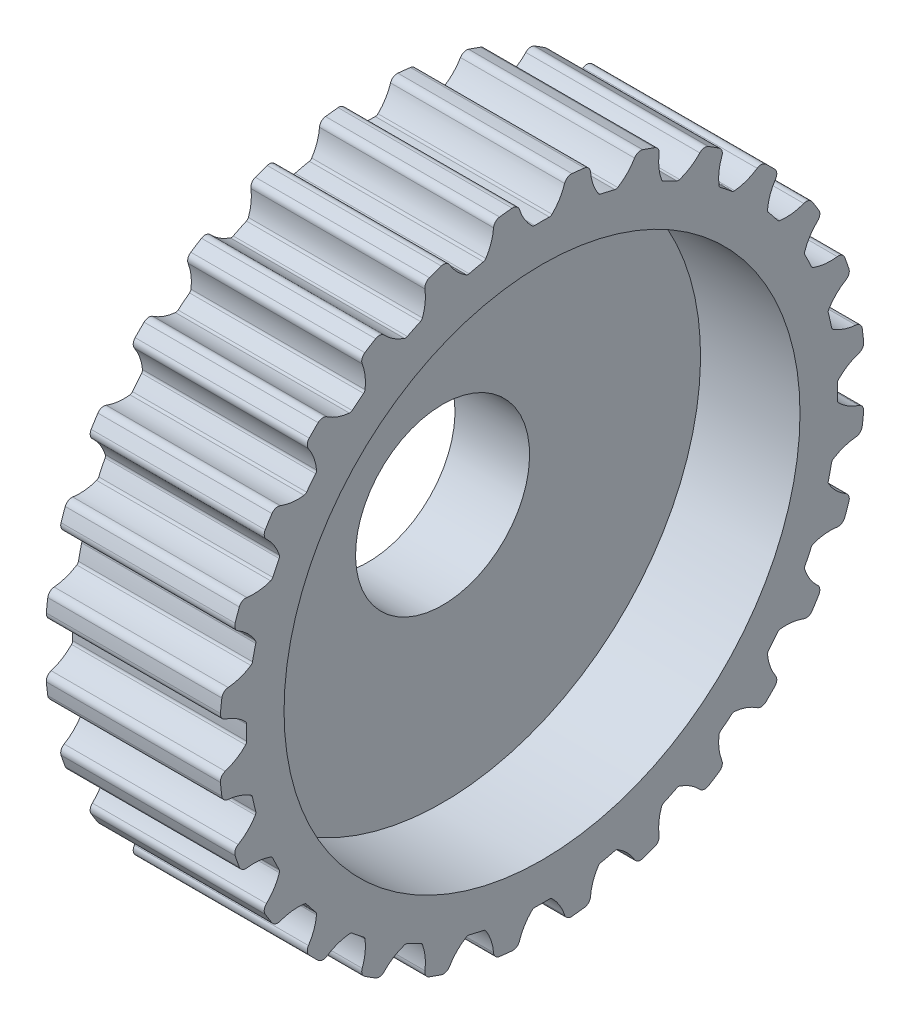
SolidWorks part; units mm, degrees
material "Vero PureWhite"
ref_plane "前视基准面" through (0, 0, 0) normal (0, 0, 1) x (1, 0, 0)
ref_plane "上视基准面" through (0, 0, 0) normal (0, 1, 0) x (1, 0, 0)
ref_plane "右视基准面" through (0, 0, 0) normal (1, 0, 0) x (0, 0, -1)
other "Configuration Table"
ref_plane "基准面1" through (0, 0, 0) normal (0, 0, 1) x (1, 0, 0)
sketch "草图1" plane through (0, 0, 0) normal (0, 0, 1) x (1, 0, 0)
  line L0 (0, 0) -> (0, 10)
  line L1 (0, 10) -> (1, 10)
  line L2 (1, 10) -> (1, 12.8583)
  line L3 (1, 12.8583) -> (0.4955, 14.7412)
  line L4 (0.4955, 14.7412) -> (1.4614, 15)
  line L5 (1.4614, 15) -> (2, 12.99)
  line L6 (2, 12.99) -> (9, 12.99)
  line L7 (9, 12.99) -> (9.5386, 15)
  line L8 (9.5386, 15) -> (10.5045, 14.7412)
  line L9 (10.5045, 14.7412) -> (10, 12.8583)
  line L10 (10, 12.8583) -> (10, 10)
  line L11 (10, 10) -> (11, 10)
  line L12 (11, 10) -> (11, 0)
  line L13 (11, 0) -> (0, 0)
  line L14 (11, 0) -> (0, 0) construction
revolve "旋转1" add sketch "草图1" angle 360 about L14
ref_plane "基准面2" through (0, 0, 0) normal (0, 0, 1) x (1, 0, 0)
sketch "草图2" plane through (0, 0, 0) normal (0, 0, 1) x (1, 0, 0)
  line L0 (0, 0) -> (0, 3.5)
  line L1 (0, 3.5) -> (11, 3.5)
  line L2 (11, 3.5) -> (11, 0)
  line L3 (11, 0) -> (0, 0)
  line L4 (11, 0) -> (0, 0) construction
  dimension "D1" = 3.5
revolve "切除-旋转1" cut sketch "草图2" angle 360 about L4
ref_plane "基准面3" through (2, 0, 0) normal (1, 0, 0) x (0, 0, -1)
sketch "草图3" plane through (2, 0, 0) normal (1, 0, 0) x (0, 0, -1)
  circle A0 centre (0, 0) radius 17.99
  arc A1 (-12.9343, 1.2013) -> (-12.7398, 0.9084) centre (-12.6555, 1.1754) ccw
  arc A2 (-12.7398, 0.9084) -> (-11.9188, 0.4022) centre (-13.3344, -0.975) cw
  arc A3 (-11.9188, 0.4022) -> (-11.8764, 0.2939) centre (-12.0263, 0.2976) cw
  arc A4 (-11.8764, 0.2939) -> (-11.8764, -0.2939) centre (0, 0) ccw
  arc A5 (-11.8764, -0.2939) -> (-11.9188, -0.4022) centre (-12.0263, -0.2976) cw
  arc A6 (-11.9188, -0.4022) -> (-12.7398, -0.9084) centre (-13.3344, 0.975) cw
  arc A7 (-12.7398, -0.9084) -> (-12.9343, -1.2013) centre (-12.6555, -1.1754) ccw
  arc A8 (-12.9343, -1.2013) -> (-12.8774, -1.707) centre (0, 0) ccw
  arc A9 (-12.8774, -1.707) -> (-12.6225, -1.9493) centre (-12.5998, -1.6702) ccw
  arc A10 (-12.6225, -1.9493) -> (-11.7095, -2.2601) centre (-12.7831, -3.9177) cw
  arc A11 (-11.7095, -2.2601) -> (-11.644, -2.3562) centre (-11.791, -2.386) cw
  arc A12 (-11.644, -2.3562) -> (-11.5132, -2.9293) centre (0, 0) ccw
  arc A13 (-11.5132, -2.9293) -> (-11.5305, -3.0443) centre (-11.6586, -2.9663) cw
  arc A14 (-11.5305, -3.0443) -> (-12.2183, -3.7205) centre (-13.217, -2.0166) cw
  arc A15 (-12.2183, -3.7205) -> (-12.3427, -4.0493) centre (-12.0767, -3.962) ccw
  arc A16 (-12.3427, -4.0493) -> (-12.1746, -4.5297) centre (0, 0) ccw
  arc A17 (-12.1746, -4.5297) -> (-11.8723, -4.7092) centre (-11.9122, -4.432) ccw
  arc A18 (-11.8723, -4.7092) -> (-10.913, -4.809) centre (-11.5908, -6.664) cw
  arc A19 (-10.913, -4.809) -> (-10.8278, -4.8882) centre (-10.9645, -4.9499) cw
  arc A20 (-10.8278, -4.8882) -> (-10.5727, -5.4178) centre (0, 0) ccw
  arc A21 (-10.5727, -5.4178) -> (-10.564, -5.5338) centre (-10.7062, -5.4862) cw
  arc A22 (-10.564, -5.5338) -> (-11.0841, -6.346) centre (-12.4369, -4.9071) cw
  arc A23 (-11.0841, -6.346) -> (-11.1322, -6.6943) centre (-10.8923, -6.55) ccw
  arc A24 (-11.1322, -6.6943) -> (-10.8615, -7.1252) centre (0, 0) ccw
  arc A25 (-10.8615, -7.1252) -> (-10.5268, -7.233) centre (-10.6273, -6.9716) ccw
  arc A26 (-10.5268, -7.233) -> (-9.5693, -7.1168) centre (-9.8174, -9.0761) cw
  arc A27 (-9.5693, -7.1168) -> (-9.4686, -7.175) centre (-9.5881, -7.2656) cw
  arc A28 (-9.4686, -7.175) -> (-9.1021, -7.6346) centre (0, 0) ccw
  arc A29 (-9.1021, -7.6346) -> (-9.0677, -7.7457) centre (-9.217, -7.731) cw
  arc A30 (-9.0677, -7.7457) -> (-9.394, -8.6534) centre (-11.0332, -7.5516) cw
  arc A31 (-9.394, -8.6534) -> (-9.3635, -9.0036) centre (-9.1617, -8.8096) ccw
  arc A32 (-9.3635, -9.0036) -> (-9.0036, -9.3635) centre (0, 0) ccw
  arc A33 (-9.0036, -9.3635) -> (-8.6534, -9.394) centre (-8.8096, -9.1617) ccw
  arc A34 (-8.6534, -9.394) -> (-7.7457, -9.0677) centre (-7.5516, -11.0332) cw
  arc A35 (-7.7457, -9.0677) -> (-7.6346, -9.1021) centre (-7.731, -9.217) cw
  arc A36 (-7.6346, -9.1021) -> (-7.175, -9.4686) centre (0, 0) ccw
  arc A37 (-7.175, -9.4686) -> (-7.1168, -9.5693) centre (-7.2656, -9.5881) cw
  arc A38 (-7.1168, -9.5693) -> (-7.233, -10.5268) centre (-9.0761, -9.8174) cw
  arc A39 (-7.233, -10.5268) -> (-7.1252, -10.8615) centre (-6.9716, -10.6273) ccw
  arc A40 (-7.1252, -10.8615) -> (-6.6943, -11.1322) centre (0, 0) ccw
  arc A41 (-6.6943, -11.1322) -> (-6.346, -11.0841) centre (-6.55, -10.8923) ccw
  arc A42 (-6.346, -11.0841) -> (-5.5338, -10.564) centre (-4.9071, -12.4369) cw
  arc A43 (-5.5338, -10.564) -> (-5.4178, -10.5727) centre (-5.4862, -10.7062) cw
  arc A44 (-5.4178, -10.5727) -> (-4.8882, -10.8278) centre (0, 0) ccw
  arc A45 (-4.8882, -10.8278) -> (-4.809, -10.913) centre (-4.9499, -10.9645) cw
  arc A46 (-4.809, -10.913) -> (-4.7092, -11.8723) centre (-6.664, -11.5908) cw
  arc A47 (-4.7092, -11.8723) -> (-4.5297, -12.1746) centre (-4.432, -11.9122) ccw
  arc A48 (-4.5297, -12.1746) -> (-4.0493, -12.3427) centre (0, 0) ccw
  arc A49 (-4.0493, -12.3427) -> (-3.7205, -12.2183) centre (-3.962, -12.0767) ccw
  arc A50 (-3.7205, -12.2183) -> (-3.0443, -11.5305) centre (-2.0166, -13.217) cw
  arc A51 (-3.0443, -11.5305) -> (-2.9293, -11.5132) centre (-2.9663, -11.6586) cw
  arc A52 (-2.9293, -11.5132) -> (-2.3562, -11.644) centre (0, 0) ccw
  arc A53 (-2.3562, -11.644) -> (-2.2601, -11.7095) centre (-2.386, -11.791) cw
  arc A54 (-2.2601, -11.7095) -> (-1.9493, -12.6225) centre (-3.9177, -12.7831) cw
  arc A55 (-1.9493, -12.6225) -> (-1.707, -12.8774) centre (-1.6702, -12.5998) ccw
  arc A56 (-1.707, -12.8774) -> (-1.2013, -12.9343) centre (0, 0) ccw
  arc A57 (-1.2013, -12.9343) -> (-0.9084, -12.7398) centre (-1.1754, -12.6555) ccw
  arc A58 (-0.9084, -12.7398) -> (-0.4022, -11.9188) centre (0.975, -13.3344) cw
  arc A59 (-0.4022, -11.9188) -> (-0.2939, -11.8764) centre (-0.2976, -12.0263) cw
  arc A60 (-0.2939, -11.8764) -> (0.2939, -11.8764) centre (0, 0) ccw
  arc A61 (0.2939, -11.8764) -> (0.4022, -11.9188) centre (0.2976, -12.0263) cw
  arc A62 (0.4022, -11.9188) -> (0.9084, -12.7398) centre (-0.975, -13.3344) cw
  arc A63 (0.9084, -12.7398) -> (1.2013, -12.9343) centre (1.1754, -12.6555) ccw
  arc A64 (1.2013, -12.9343) -> (1.707, -12.8774) centre (0, 0) ccw
  arc A65 (1.707, -12.8774) -> (1.9493, -12.6225) centre (1.6702, -12.5998) ccw
  arc A66 (1.9493, -12.6225) -> (2.2601, -11.7095) centre (3.9177, -12.7831) cw
  arc A67 (2.2601, -11.7095) -> (2.3562, -11.644) centre (2.386, -11.791) cw
  arc A68 (2.3562, -11.644) -> (2.9293, -11.5132) centre (0, 0) ccw
  arc A69 (2.9293, -11.5132) -> (3.0443, -11.5305) centre (2.9663, -11.6586) cw
  arc A70 (3.0443, -11.5305) -> (3.7205, -12.2183) centre (2.0166, -13.217) cw
  arc A71 (3.7205, -12.2183) -> (4.0493, -12.3427) centre (3.962, -12.0767) ccw
  arc A72 (4.0493, -12.3427) -> (4.5297, -12.1746) centre (0, 0) ccw
  arc A73 (4.5297, -12.1746) -> (4.7092, -11.8723) centre (4.432, -11.9122) ccw
  arc A74 (4.7092, -11.8723) -> (4.809, -10.913) centre (6.664, -11.5908) cw
  arc A75 (4.809, -10.913) -> (4.8882, -10.8278) centre (4.9499, -10.9645) cw
  arc A76 (4.8882, -10.8278) -> (5.4178, -10.5727) centre (0, 0) ccw
  arc A77 (5.4178, -10.5727) -> (5.5338, -10.564) centre (5.4862, -10.7062) cw
  arc A78 (5.5338, -10.564) -> (6.346, -11.0841) centre (4.9071, -12.4369) cw
  arc A79 (6.346, -11.0841) -> (6.6943, -11.1322) centre (6.55, -10.8923) ccw
  arc A80 (6.6943, -11.1322) -> (7.1252, -10.8615) centre (0, 0) ccw
  arc A81 (7.1252, -10.8615) -> (7.233, -10.5268) centre (6.9716, -10.6273) ccw
  arc A82 (7.233, -10.5268) -> (7.1168, -9.5693) centre (9.0761, -9.8174) cw
  arc A83 (7.1168, -9.5693) -> (7.175, -9.4686) centre (7.2656, -9.5881) cw
  arc A84 (7.175, -9.4686) -> (7.6346, -9.1021) centre (0, 0) ccw
  arc A85 (7.6346, -9.1021) -> (7.7457, -9.0677) centre (7.731, -9.217) cw
  arc A86 (7.7457, -9.0677) -> (8.6534, -9.394) centre (7.5516, -11.0332) cw
  arc A87 (8.6534, -9.394) -> (9.0036, -9.3635) centre (8.8096, -9.1617) ccw
  arc A88 (9.0036, -9.3635) -> (9.3635, -9.0036) centre (0, 0) ccw
  arc A89 (9.3635, -9.0036) -> (9.394, -8.6534) centre (9.1617, -8.8096) ccw
  arc A90 (9.394, -8.6534) -> (9.0677, -7.7457) centre (11.0332, -7.5516) cw
  arc A91 (9.0677, -7.7457) -> (9.1021, -7.6346) centre (9.217, -7.731) cw
  arc A92 (9.1021, -7.6346) -> (9.4686, -7.175) centre (0, 0) ccw
  arc A93 (9.4686, -7.175) -> (9.5693, -7.1168) centre (9.5881, -7.2656) cw
  arc A94 (9.5693, -7.1168) -> (10.5268, -7.233) centre (9.8174, -9.0761) cw
  arc A95 (10.5268, -7.233) -> (10.8615, -7.1252) centre (10.6273, -6.9716) ccw
  arc A96 (10.8615, -7.1252) -> (11.1322, -6.6943) centre (0, 0) ccw
  arc A97 (11.1322, -6.6943) -> (11.0841, -6.346) centre (10.8923, -6.55) ccw
  arc A98 (11.0841, -6.346) -> (10.564, -5.5338) centre (12.4369, -4.9071) cw
  arc A99 (10.564, -5.5338) -> (10.5727, -5.4178) centre (10.7062, -5.4862) cw
  arc A100 (10.5727, -5.4178) -> (10.8278, -4.8882) centre (0, 0) ccw
  arc A101 (10.8278, -4.8882) -> (10.913, -4.809) centre (10.9645, -4.9499) cw
  arc A102 (10.913, -4.809) -> (11.8723, -4.7092) centre (11.5908, -6.664) cw
  arc A103 (11.8723, -4.7092) -> (12.1746, -4.5297) centre (11.9122, -4.432) ccw
  arc A104 (12.1746, -4.5297) -> (12.3427, -4.0493) centre (0, 0) ccw
  arc A105 (12.3427, -4.0493) -> (12.2183, -3.7205) centre (12.0767, -3.962) ccw
  arc A106 (12.2183, -3.7205) -> (11.5305, -3.0443) centre (13.217, -2.0166) cw
  arc A107 (11.5305, -3.0443) -> (11.5132, -2.9293) centre (11.6586, -2.9663) cw
  arc A108 (11.5132, -2.9293) -> (11.644, -2.3562) centre (0, 0) ccw
  arc A109 (11.644, -2.3562) -> (11.7095, -2.2601) centre (11.791, -2.386) cw
  arc A110 (11.7095, -2.2601) -> (12.6225, -1.9493) centre (12.7831, -3.9177) cw
  arc A111 (12.6225, -1.9493) -> (12.8774, -1.707) centre (12.5998, -1.6702) ccw
  arc A112 (12.8774, -1.707) -> (12.9343, -1.2013) centre (0, 0) ccw
  arc A113 (12.9343, -1.2013) -> (12.7398, -0.9084) centre (12.6555, -1.1754) ccw
  arc A114 (12.7398, -0.9084) -> (11.9188, -0.4022) centre (13.3344, 0.975) cw
  arc A115 (11.9188, -0.4022) -> (11.8764, -0.2939) centre (12.0263, -0.2976) cw
  arc A116 (11.8764, -0.2939) -> (11.8764, 0.2939) centre (0, 0) ccw
  arc A117 (11.8764, 0.2939) -> (11.9188, 0.4022) centre (12.0263, 0.2976) cw
  arc A118 (11.9188, 0.4022) -> (12.7398, 0.9084) centre (13.3344, -0.975) cw
  arc A119 (12.7398, 0.9084) -> (12.9343, 1.2013) centre (12.6555, 1.1754) ccw
  arc A120 (12.9343, 1.2013) -> (12.8774, 1.707) centre (0, 0) ccw
  arc A121 (12.8774, 1.707) -> (12.6225, 1.9493) centre (12.5998, 1.6702) ccw
  arc A122 (12.6225, 1.9493) -> (11.7095, 2.2601) centre (12.7831, 3.9177) cw
  arc A123 (11.7095, 2.2601) -> (11.644, 2.3562) centre (11.791, 2.386) cw
  arc A124 (11.644, 2.3562) -> (11.5132, 2.9293) centre (0, 0) ccw
  arc A125 (11.5132, 2.9293) -> (11.5305, 3.0443) centre (11.6586, 2.9663) cw
  arc A126 (11.5305, 3.0443) -> (12.2183, 3.7205) centre (13.217, 2.0166) cw
  arc A127 (12.2183, 3.7205) -> (12.3427, 4.0493) centre (12.0767, 3.962) ccw
  arc A128 (12.3427, 4.0493) -> (12.1746, 4.5297) centre (0, 0) ccw
  arc A129 (12.1746, 4.5297) -> (11.8723, 4.7092) centre (11.9122, 4.432) ccw
  arc A130 (11.8723, 4.7092) -> (10.913, 4.809) centre (11.5908, 6.664) cw
  arc A131 (10.913, 4.809) -> (10.8278, 4.8882) centre (10.9645, 4.9499) cw
  arc A132 (10.8278, 4.8882) -> (10.5727, 5.4178) centre (0, 0) ccw
  arc A133 (10.5727, 5.4178) -> (10.564, 5.5338) centre (10.7062, 5.4862) cw
  arc A134 (10.564, 5.5338) -> (11.0841, 6.346) centre (12.4369, 4.9071) cw
  arc A135 (11.0841, 6.346) -> (11.1322, 6.6943) centre (10.8923, 6.55) ccw
  arc A136 (11.1322, 6.6943) -> (10.8615, 7.1252) centre (0, 0) ccw
  arc A137 (10.8615, 7.1252) -> (10.5268, 7.233) centre (10.6273, 6.9716) ccw
  arc A138 (10.5268, 7.233) -> (9.5693, 7.1168) centre (9.8174, 9.0761) cw
  arc A139 (9.5693, 7.1168) -> (9.4686, 7.175) centre (9.5881, 7.2656) cw
  arc A140 (9.4686, 7.175) -> (9.1021, 7.6346) centre (0, 0) ccw
  arc A141 (9.1021, 7.6346) -> (9.0677, 7.7457) centre (9.217, 7.731) cw
  arc A142 (9.0677, 7.7457) -> (9.394, 8.6534) centre (11.0332, 7.5516) cw
  arc A143 (9.394, 8.6534) -> (9.3635, 9.0036) centre (9.1617, 8.8096) ccw
  arc A144 (9.3635, 9.0036) -> (9.0036, 9.3635) centre (0, 0) ccw
  arc A145 (9.0036, 9.3635) -> (8.6534, 9.394) centre (8.8096, 9.1617) ccw
  arc A146 (8.6534, 9.394) -> (7.7457, 9.0677) centre (7.5516, 11.0332) cw
  arc A147 (7.7457, 9.0677) -> (7.6346, 9.1021) centre (7.731, 9.217) cw
  arc A148 (7.6346, 9.1021) -> (7.175, 9.4686) centre (0, 0) ccw
  arc A149 (7.175, 9.4686) -> (7.1168, 9.5693) centre (7.2656, 9.5881) cw
  arc A150 (7.1168, 9.5693) -> (7.233, 10.5268) centre (9.0761, 9.8174) cw
  arc A151 (7.233, 10.5268) -> (7.1252, 10.8615) centre (6.9716, 10.6273) ccw
  arc A152 (7.1252, 10.8615) -> (6.6943, 11.1322) centre (0, 0) ccw
  arc A153 (6.6943, 11.1322) -> (6.346, 11.0841) centre (6.55, 10.8923) ccw
  arc A154 (6.346, 11.0841) -> (5.5338, 10.564) centre (4.9071, 12.4369) cw
  arc A155 (5.5338, 10.564) -> (5.4178, 10.5727) centre (5.4862, 10.7062) cw
  arc A156 (5.4178, 10.5727) -> (4.8882, 10.8278) centre (0, 0) ccw
  arc A157 (4.8882, 10.8278) -> (4.809, 10.913) centre (4.9499, 10.9645) cw
  arc A158 (4.809, 10.913) -> (4.7092, 11.8723) centre (6.664, 11.5908) cw
  arc A159 (4.7092, 11.8723) -> (4.5297, 12.1746) centre (4.432, 11.9122) ccw
  arc A160 (4.5297, 12.1746) -> (4.0493, 12.3427) centre (0, 0) ccw
  arc A161 (4.0493, 12.3427) -> (3.7205, 12.2183) centre (3.962, 12.0767) ccw
  arc A162 (3.7205, 12.2183) -> (3.0443, 11.5305) centre (2.0166, 13.217) cw
  arc A163 (3.0443, 11.5305) -> (2.9293, 11.5132) centre (2.9663, 11.6586) cw
  arc A164 (2.9293, 11.5132) -> (2.3562, 11.644) centre (0, 0) ccw
  arc A165 (2.3562, 11.644) -> (2.2601, 11.7095) centre (2.386, 11.791) cw
  arc A166 (2.2601, 11.7095) -> (1.9493, 12.6225) centre (3.9177, 12.7831) cw
  arc A167 (1.9493, 12.6225) -> (1.707, 12.8774) centre (1.6702, 12.5998) ccw
  arc A168 (1.707, 12.8774) -> (1.2013, 12.9343) centre (0, 0) ccw
  arc A169 (1.2013, 12.9343) -> (0.9084, 12.7398) centre (1.1754, 12.6555) ccw
  arc A170 (0.9084, 12.7398) -> (0.4022, 11.9188) centre (-0.975, 13.3344) cw
  arc A171 (0.4022, 11.9188) -> (0.2939, 11.8764) centre (0.2976, 12.0263) cw
  arc A172 (0.2939, 11.8764) -> (-0.2939, 11.8764) centre (0, 0) ccw
  arc A173 (-0.2939, 11.8764) -> (-0.4022, 11.9188) centre (-0.2976, 12.0263) cw
  arc A174 (-0.4022, 11.9188) -> (-0.9084, 12.7398) centre (0.975, 13.3344) cw
  arc A175 (-0.9084, 12.7398) -> (-1.2013, 12.9343) centre (-1.1754, 12.6555) ccw
  arc A176 (-1.2013, 12.9343) -> (-1.707, 12.8774) centre (0, 0) ccw
  arc A177 (-1.707, 12.8774) -> (-1.9493, 12.6225) centre (-1.6702, 12.5998) ccw
  arc A178 (-1.9493, 12.6225) -> (-2.2601, 11.7095) centre (-3.9177, 12.7831) cw
  arc A179 (-2.2601, 11.7095) -> (-2.3562, 11.644) centre (-2.386, 11.791) cw
  arc A180 (-2.3562, 11.644) -> (-2.9293, 11.5132) centre (0, 0) ccw
  arc A181 (-2.9293, 11.5132) -> (-3.0443, 11.5305) centre (-2.9663, 11.6586) cw
  arc A182 (-3.0443, 11.5305) -> (-3.7205, 12.2183) centre (-2.0166, 13.217) cw
  arc A183 (-3.7205, 12.2183) -> (-4.0493, 12.3427) centre (-3.962, 12.0767) ccw
  arc A184 (-4.0493, 12.3427) -> (-4.5297, 12.1746) centre (0, 0) ccw
  arc A185 (-4.5297, 12.1746) -> (-4.7092, 11.8723) centre (-4.432, 11.9122) ccw
  arc A186 (-4.7092, 11.8723) -> (-4.809, 10.913) centre (-6.664, 11.5908) cw
  arc A187 (-4.809, 10.913) -> (-4.8882, 10.8278) centre (-4.9499, 10.9645) cw
  arc A188 (-4.8882, 10.8278) -> (-5.4178, 10.5727) centre (0, 0) ccw
  arc A189 (-5.4178, 10.5727) -> (-5.5338, 10.564) centre (-5.4862, 10.7062) cw
  arc A190 (-5.5338, 10.564) -> (-6.346, 11.0841) centre (-4.9071, 12.4369) cw
  arc A191 (-6.346, 11.0841) -> (-6.6943, 11.1322) centre (-6.55, 10.8923) ccw
  arc A192 (-6.6943, 11.1322) -> (-7.1252, 10.8615) centre (0, 0) ccw
  arc A193 (-7.1252, 10.8615) -> (-7.233, 10.5268) centre (-6.9716, 10.6273) ccw
  arc A194 (-7.233, 10.5268) -> (-7.1168, 9.5693) centre (-9.0761, 9.8174) cw
  arc A195 (-7.1168, 9.5693) -> (-7.175, 9.4686) centre (-7.2656, 9.5881) cw
  arc A196 (-7.175, 9.4686) -> (-7.6346, 9.1021) centre (0, 0) ccw
  arc A197 (-7.6346, 9.1021) -> (-7.7457, 9.0677) centre (-7.731, 9.217) cw
  arc A198 (-7.7457, 9.0677) -> (-8.6534, 9.394) centre (-7.5516, 11.0332) cw
  arc A199 (-8.6534, 9.394) -> (-9.0036, 9.3635) centre (-8.8096, 9.1617) ccw
  arc A200 (-9.0036, 9.3635) -> (-9.3635, 9.0036) centre (0, 0) ccw
  arc A201 (-9.3635, 9.0036) -> (-9.394, 8.6534) centre (-9.1617, 8.8096) ccw
  arc A202 (-9.394, 8.6534) -> (-9.0677, 7.7457) centre (-11.0332, 7.5516) cw
  arc A203 (-9.0677, 7.7457) -> (-9.1021, 7.6346) centre (-9.217, 7.731) cw
  arc A204 (-9.1021, 7.6346) -> (-9.4686, 7.175) centre (0, 0) ccw
  arc A205 (-9.4686, 7.175) -> (-9.5693, 7.1168) centre (-9.5881, 7.2656) cw
  arc A206 (-9.5693, 7.1168) -> (-10.5268, 7.233) centre (-9.8174, 9.0761) cw
  arc A207 (-10.5268, 7.233) -> (-10.8615, 7.1252) centre (-10.6273, 6.9716) ccw
  arc A208 (-10.8615, 7.1252) -> (-11.1322, 6.6943) centre (0, 0) ccw
  arc A209 (-11.1322, 6.6943) -> (-11.0841, 6.346) centre (-10.8923, 6.55) ccw
  arc A210 (-11.0841, 6.346) -> (-10.564, 5.5338) centre (-12.4369, 4.9071) cw
  arc A211 (-10.564, 5.5338) -> (-10.5727, 5.4178) centre (-10.7062, 5.4862) cw
  arc A212 (-10.5727, 5.4178) -> (-10.8278, 4.8882) centre (0, 0) ccw
  arc A213 (-10.8278, 4.8882) -> (-10.913, 4.809) centre (-10.9645, 4.9499) cw
  arc A214 (-10.913, 4.809) -> (-11.8723, 4.7092) centre (-11.5908, 6.664) cw
  arc A215 (-11.8723, 4.7092) -> (-12.1746, 4.5297) centre (-11.9122, 4.432) ccw
  arc A216 (-12.1746, 4.5297) -> (-12.3427, 4.0493) centre (0, 0) ccw
  arc A217 (-12.3427, 4.0493) -> (-12.2183, 3.7205) centre (-12.0767, 3.962) ccw
  arc A218 (-12.2183, 3.7205) -> (-11.5305, 3.0443) centre (-13.217, 2.0166) cw
  arc A219 (-11.5305, 3.0443) -> (-11.5132, 2.9293) centre (-11.6586, 2.9663) cw
  arc A220 (-11.5132, 2.9293) -> (-11.644, 2.3562) centre (0, 0) ccw
  arc A221 (-11.644, 2.3562) -> (-11.7095, 2.2601) centre (-11.791, 2.386) cw
  arc A222 (-11.7095, 2.2601) -> (-12.6225, 1.9493) centre (-12.7831, 3.9177) cw
  arc A223 (-12.6225, 1.9493) -> (-12.8774, 1.707) centre (-12.5998, 1.6702) ccw
  arc A224 (-12.8774, 1.707) -> (-12.9343, 1.2013) centre (0, 0) ccw
extrude "切除-拉伸1" cut sketch "草图3" along normal blind 7
sketch "草图4" plane through (0, 0, 0) normal (0, 0, 1) x (1, 0, 0)
  line L1 (-9.3365, 55.092) -> (2, 55.092)
  line L2 (-9.3365, 55.092) -> (-9.3365, -19.7557)
  line L3 (-9.3365, -19.7557) -> (2, -19.7557)
  line L4 (2, 55.092) -> (2, -19.7557)
  line L5 (-9.3365, 55.092) -> (2, -19.7557) construction
  line L6 (-9.3365, -19.7557) -> (2, 55.092) construction
  line L7 (24.9109, 51.9429) -> (9, 51.9429)
  line L8 (24.9109, 51.9429) -> (24.9109, -20.1203)
  line L9 (24.9109, -20.1203) -> (9, -20.1203)
  line L10 (9, 51.9429) -> (9, -20.1203)
  line L11 (24.9109, 51.9429) -> (9, -20.1203) construction
  line L12 (24.9109, -20.1203) -> (9, 51.9429) construction
  point P0 (-3.6683, 17.6681)
  point P5 (16.9555, 15.9113)
extrude "切除-拉伸2" cut sketch "草图4" against normal through all both and the other way through all
sketch "草图5" plane through (9, 0, 0) normal (1, 0, 0) x (0, 0, -1)
  circle A0 centre (0, 0) radius 10.375
  dimension "D1" = 20.75
extrude "切除-拉伸3" cut sketch "草图5" against normal offset from surface 3 and the other way through all up to face at (2, 3.5, 0)
